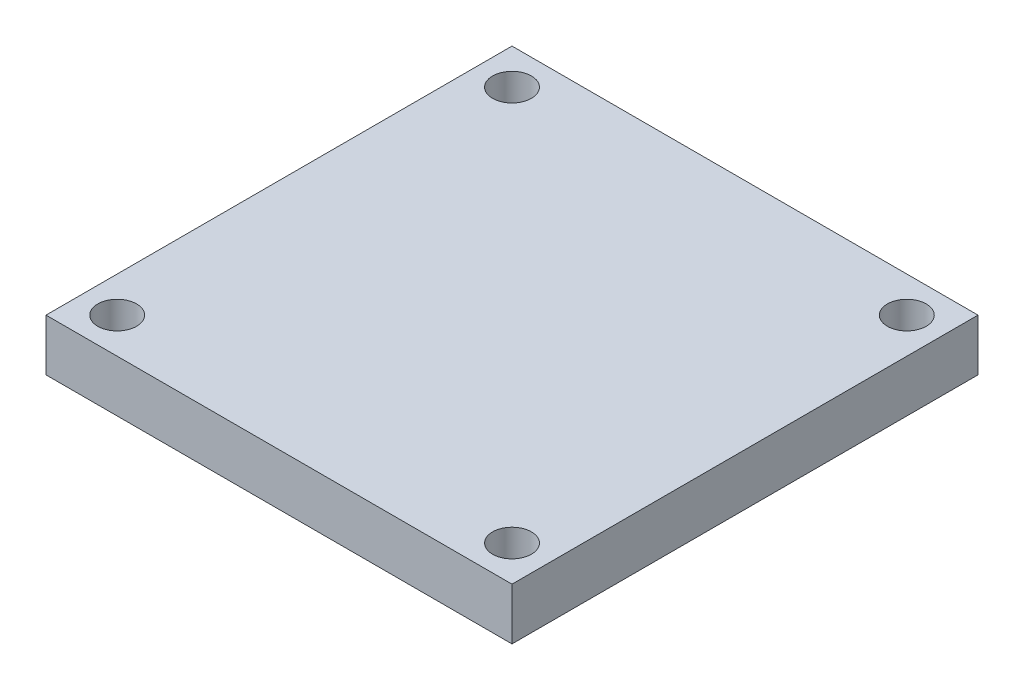
SolidWorks part; units mm, degrees
ref_plane "Front Plane" through (0, 0, 0) normal (0, 0, 1) x (1, 0, 0)
ref_plane "Top Plane" through (0, 0, 0) normal (0, 1, 0) x (1, 0, 0)
ref_plane "Right Plane" through (0, 0, 0) normal (1, 0, 0) x (0, 0, -1)
sketch "Sketch1" plane through (0, 0, 0) normal (0, 1, 0) x (1, 0, 0)
  line L1 (18, -18) -> (-18, -18)
  line L2 (18, -18) -> (18, 18)
  line L3 (18, 18) -> (-18, 18)
  line L4 (-18, -18) -> (-18, 18)
  line L5 (18, -18) -> (-18, 18) construction
  line L6 (18, 18) -> (-18, -18) construction
  point P0 (0, 0)
  dimension "D1" = 36
extrude "Boss-Extrude1" add sketch "Sketch1" along normal blind 4
sketch "Sketch2" plane through (0, 4, 0) normal (0, 1, 0) x (1, 0, 0)
  line L1 (15.25, -15.25) -> (-15.25, -15.25)
  line L2 (15.25, -15.25) -> (15.25, 15.25)
  line L3 (15.25, 15.25) -> (-15.25, 15.25)
  line L4 (-15.25, -15.25) -> (-15.25, 15.25)
  line L5 (15.25, -15.25) -> (-15.25, 15.25) construction
  line L6 (15.25, 15.25) -> (-15.25, -15.25) construction
  point P0 (0, 0)
  point P7 (-15.25, -15.25)
  point P8 (-15.25, 15.25)
  point P9 (15.25, -15.25)
  point P10 (15.25, 15.25)
  dimension "D1" = 30.5
hole_wizard "Ø3.0mm Press Dowel Hole1" positions "Sketch3" profile "Sketch4" hole size "Ø3.0" standard "ANSI Metric" end condition through all
sketch "Sketch3" plane through (0, 4, 0) normal (0, 1, 0) x (1, 0, 0)
  point P0 (-15.25, 15.25)
  point P3 (15.25, 15.25)
  point P6 (15.25, -15.25)
  point P9 (-15.25, -15.25)
sketch "Sketch4" plane through (-15.25, 4, -15.25) normal (1, 0, 0) x (0, 0, 1)
  line L0 (0, 0) -> (0, 4)
  line L1 (0, 4) -> (1.5, 4)
  line L2 (1.5, 4) -> (1.5, 0)
  line L5 (1.5, 0) -> (0, 0)
  line L11 (0, -6.35) -> (0, 107.95) construction
  dimension "Thru Hole Dia." = 3
  dimension "Thru Hole Depth" = 4
